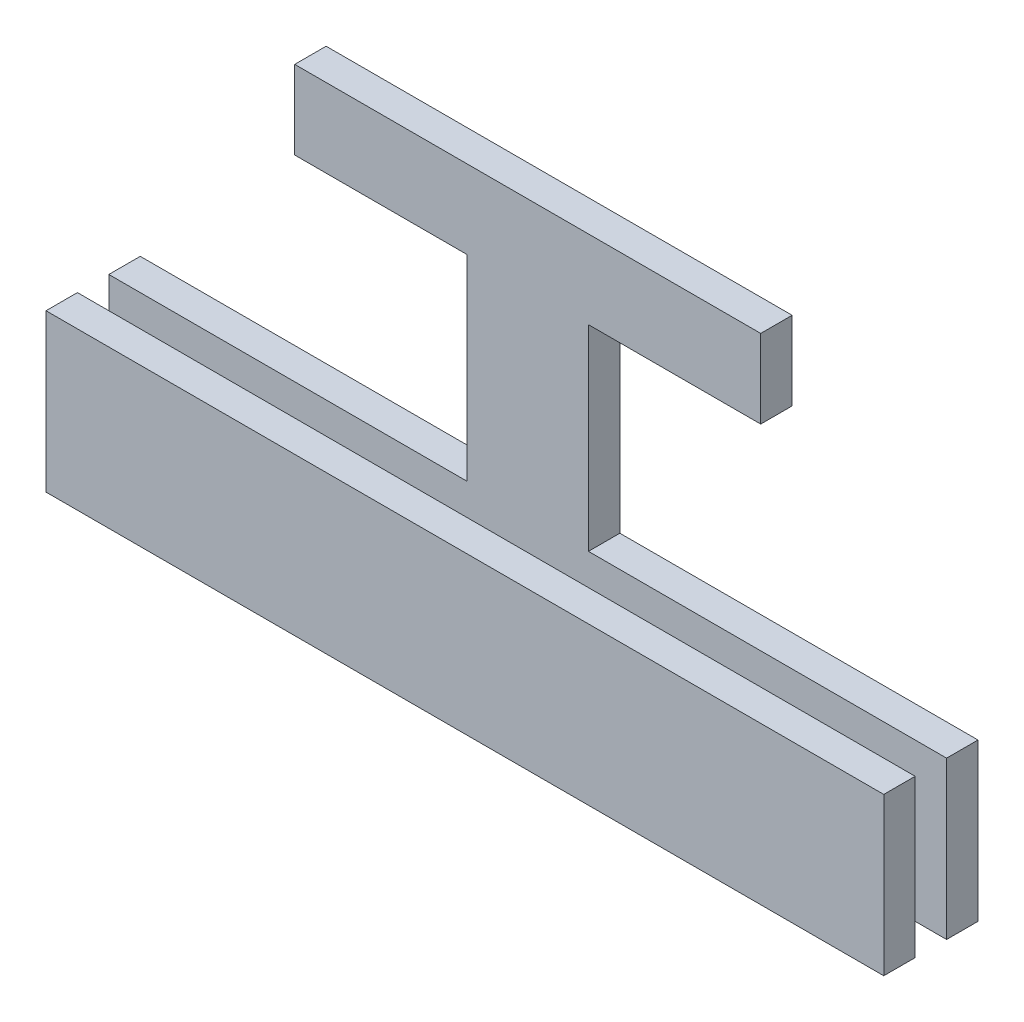
SolidWorks part; units mm, degrees
ref_plane "Ön Düzlem" through (0, 0, 0) normal (0, 0, 1) x (1, 0, 0)
ref_plane "Üst Düzlem" through (0, 0, 0) normal (0, 1, 0) x (1, 0, 0)
ref_plane "Sağ Düzlem" through (0, 0, 0) normal (1, 0, 0) x (0, 0, -1)
sketch "Sketch1" plane through (0, 0, 0) normal (0, 0, 1) x (1, 0, 0)
  line L2 (40, -7.5) -> (-40, -7.5)
  line L3 (40, -7.5) -> (40, 7.5)
  line L4 (40, 7.5) -> (-40, 7.5)
  line L5 (-40, -7.5) -> (-40, 7.5)
  line L6 (40, -7.5) -> (-40, 7.5) construction
  line L7 (40, 7.5) -> (-40, -7.5) construction
  dimension "D1" = 15
  dimension "D2" = 80
ref_plane "Plane1" through (0, -7.5, 0) normal (0, 1, 0) x (1, 0, 0)
sketch "Sketch2" plane through (0, -7.5, 0) normal (0, 1, 0) x (1, 0, 0)
  line L1 (-40, 0) -> (40, 0)
  line L2 (-40, 0) -> (-40, 3)
  line L3 (-40, 3) -> (40, 3)
  line L4 (40, 0) -> (40, 3)
  dimension "D1" = 80
  dimension "D2" = 3
ref_plane "Plane2" through (0, 0, -3) normal (0, 0, -1) x (-1, 0, 0)
sketch "Sketch3" plane through (0, 0, -3) normal (0, 0, -1) x (-1, 0, 0)
  line L1 (40, -7.5) -> (-40, -7.5)
  line L2 (40, -7.5) -> (40, 7.5)
  line L3 (40, 7.5) -> (5.8, 7.5)
  line L4 (-40, -7.5) -> (-40, 7.5)
  line L6 (22.25, 26.25) -> (5.8, 26.25)
  line L7 (22.25, 26.25) -> (22.25, 33.75)
  line L8 (22.25, 33.75) -> (-22.25, 33.75)
  line L9 (-22.25, 26.25) -> (-22.25, 33.75)
  line L10 (22.25, 26.25) -> (-22.25, 33.75) construction
  line L11 (22.25, 33.75) -> (-22.25, 26.25) construction
  line L12 (-5.8, 7.5) -> (-40, 7.5)
  line L14 (-5.8, 26.25) -> (-22.25, 26.25)
  line L16 (-5.8, 26.25) -> (-5.8, 7.5)
  line L18 (5.8, 26.25) -> (5.8, 7.5)
  point P5 (0, 30)
  dimension "D1" = 80
  dimension "D2" = 15
  dimension "D3" = 44.5
  dimension "D4" = 7.5
extrude "Boss-Extrude1" add sketch "Sketch1" along normal blind 3
extrude "Boss-Extrude2" add sketch "Sketch3" along normal blind 3 separate body
